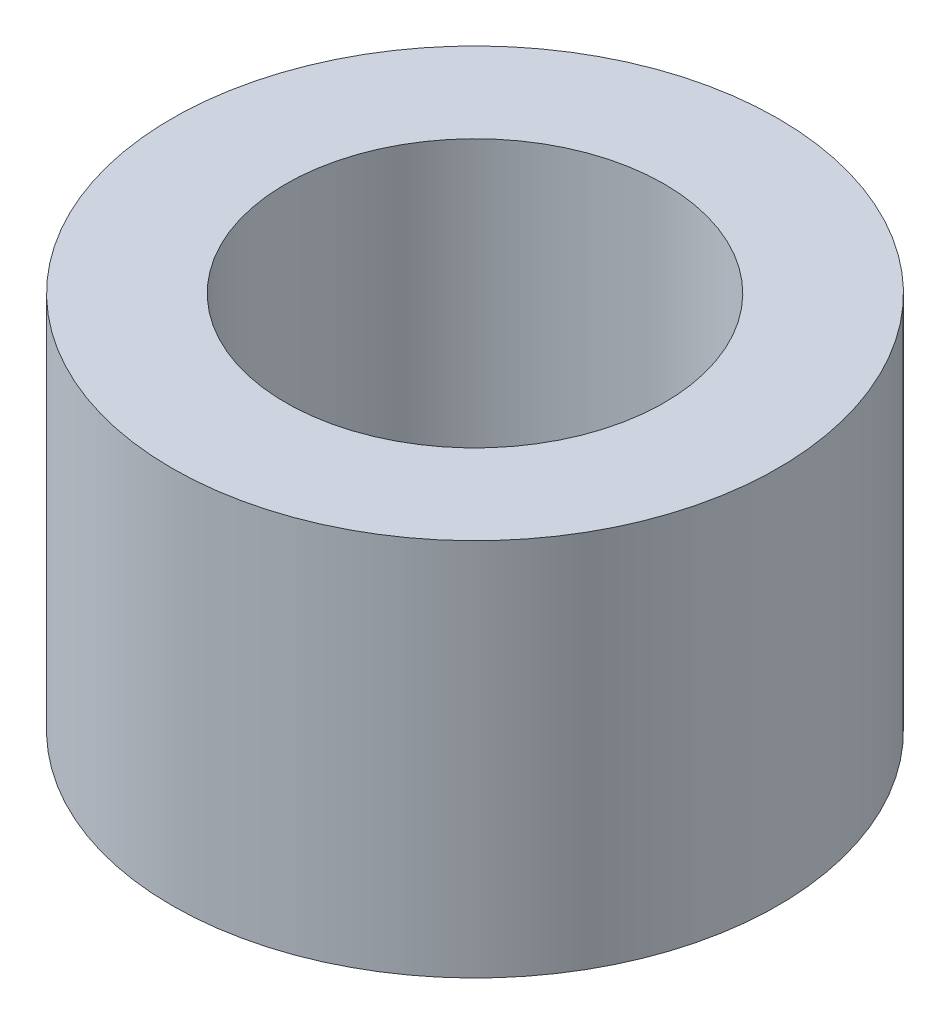
SolidWorks part; units mm, degrees
material "Nylon 6/10"
ref_plane "Front Plane" through (0, 0, 0) normal (0, 0, 1) x (1, 0, 0)
ref_plane "Top Plane" through (0, 0, 0) normal (0, 1, 0) x (1, 0, 0)
ref_plane "Right Plane" through (0, 0, 0) normal (1, 0, 0) x (0, 0, -1)
sketch "Sketch1" plane through (0, 0, 0) normal (0, 1, 0) x (1, 0, 0)
  circle A0 centre (0, 0) radius 2.3813
  circle A1 centre (0, 0) radius 3.81
  dimension "D1" = 4.7625
  dimension "D2" = 7.62
extrude "Boss-Extrude1" add sketch "Sketch1" along normal blind 4.7625
